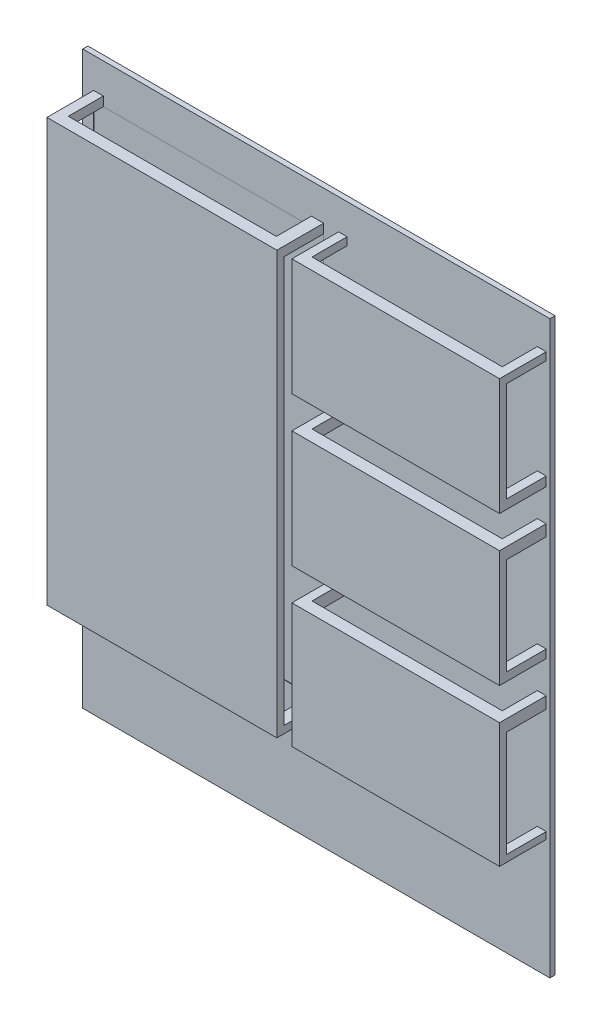
SolidWorks part; units mm, degrees
ref_plane "Front Plane" through (0, 0, 0) normal (0, 0, 1) x (1, 0, 0)
ref_plane "Top Plane" through (0, 0, 0) normal (0, 1, 0) x (1, 0, 0)
ref_plane "Right Plane" through (0, 0, 0) normal (1, 0, 0) x (0, 0, -1)
sketch "Sketch1" plane through (0, 0, 0) normal (0, 0, 1) x (1, 0, 0)
  line L1 (0, 0) -> (180, 0)
  line L2 (0, 0) -> (0, 220)
  line L3 (0, 220) -> (180, 220)
  line L4 (180, 0) -> (180, 220)
  dimension "D1" = 220
  dimension "D2" = 180
extrude "Base" add sketch "Sketch1" along normal blind 2
sketch "Sketch2" plane through (0, 0, 0) normal (0, 0, 1) x (1, 0, 0)
  line L0 (138.5962, 163.278) -> (138.5962, 150.8827) construction
  line L1 (4.2054, 208.278) -> (92.8124, 208.278)
  line L2 (4.2054, 208.278) -> (4.2054, 45.5305)
  line L3 (4.2054, 45.5305) -> (92.8124, 45.5305)
  line L4 (92.8124, 208.278) -> (92.8124, 45.5305)
  line L5 (98.5962, 208.278) -> (178.5962, 208.278)
  line L6 (98.5962, 208.278) -> (98.5962, 163.278)
  line L7 (98.5962, 163.278) -> (178.5962, 163.278)
  line L8 (178.5962, 208.278) -> (178.5962, 163.278)
  line L9 (98.5962, 150.8827) -> (178.5962, 150.8827)
  line L10 (98.5962, 150.8827) -> (98.5962, 105.8827)
  line L11 (98.5962, 105.8827) -> (178.5962, 105.8827)
  line L12 (178.5962, 150.8827) -> (178.5962, 105.8827)
  line L13 (98.5962, 93.4873) -> (178.5962, 93.4873)
  line L14 (98.5962, 93.4873) -> (98.5962, 45.5305)
  line L15 (98.5962, 45.5305) -> (178.5962, 45.5305)
  line L16 (178.5962, 93.4873) -> (178.5962, 45.5305)
  line L17 (138.5962, 105.8827) -> (138.5962, 93.4873) construction
  dimension "D1" = 80
  dimension "D2" = 45
extrude "Boards" add sketch "Sketch2" along normal blind 20
sketch "Sketch3" plane through (0, 0, 0) normal (0, 1, 0) x (1, 0, 0)
  line L1 (7.9453, -2) -> (88.1137, -2)
  line L2 (7.9453, -2) -> (7.9453, -15.4977)
  line L3 (7.9453, -15.4977) -> (88.1137, -15.4977)
  line L4 (88.1137, -2) -> (88.1137, -15.4977)
  line L5 (180, -2) -> (0, -2) construction
  line L6 (101.8568, -2) -> (175.1537, -2)
  line L7 (101.8568, -2) -> (101.8568, -15.4977)
  line L8 (101.8568, -15.4977) -> (175.1537, -15.4977)
  line L9 (175.1537, -2) -> (175.1537, -15.4977)
extrude "Cut-Extrude1" cut sketch "Sketch3" along normal through all both and the other way through all
sketch "Sketch4" plane through (92.8124, 0, 0) normal (1, 0, 0) x (0, 0, -1)
  line L1 (-17.2458, 204.7288) -> (-1.8485, 204.7288)
  line L2 (-17.2458, 204.7288) -> (-17.2458, 48.3037)
  line L3 (-17.2458, 48.3037) -> (-1.8485, 48.3037)
  line L4 (-1.8485, 204.7288) -> (-1.8485, 48.3037)
extrude "Cut-Extrude2" cut sketch "Sketch4" against normal up to surface (88.607 mm away) from surface at 0 up to face at (4.2054, 126.9042, 11) starting at face at (92.8124, 126.9042, 11)
sketch "Sketch5" plane through (178.5962, 0, 0) normal (1, 0, 0) x (0, 0, -1)
  line L0 (-17.2458, 204.7288) -> (-17.2458, 48.3037) construction
  line L1 (-17.2458, 166.797) -> (-2, 166.797)
  line L2 (-17.2458, 166.797) -> (-17.2458, 205.2622)
  line L3 (-17.2458, 205.2622) -> (-2, 205.2622)
  line L4 (-2, 166.797) -> (-2, 205.2622)
  line L5 (-2, 163.278) -> (-2, 208.278) construction
  line L6 (-2, 0) -> (-2, 220) construction
  line L7 (-17.2458, 146.5367) -> (-2, 146.5367)
  line L8 (-17.2458, 146.5367) -> (-17.2458, 109.0992)
  line L9 (-17.2458, 109.0992) -> (-2, 109.0992)
  line L10 (-2, 146.5367) -> (-2, 109.0992)
  line L12 (-17.2458, 88.9857) -> (-2, 88.9857)
  line L13 (-17.2458, 88.9857) -> (-17.2458, 48.1715)
  line L14 (-17.2458, 48.1715) -> (-2, 48.1715)
  line L15 (-2, 88.9857) -> (-2, 48.1715)
extrude "Cut-Extrude3" cut sketch "Sketch5" against normal up to surface (80 mm away) from surface at 0 up to face at (98.5962, 185.778, 11) starting at face at (178.5962, 185.778, 11)
